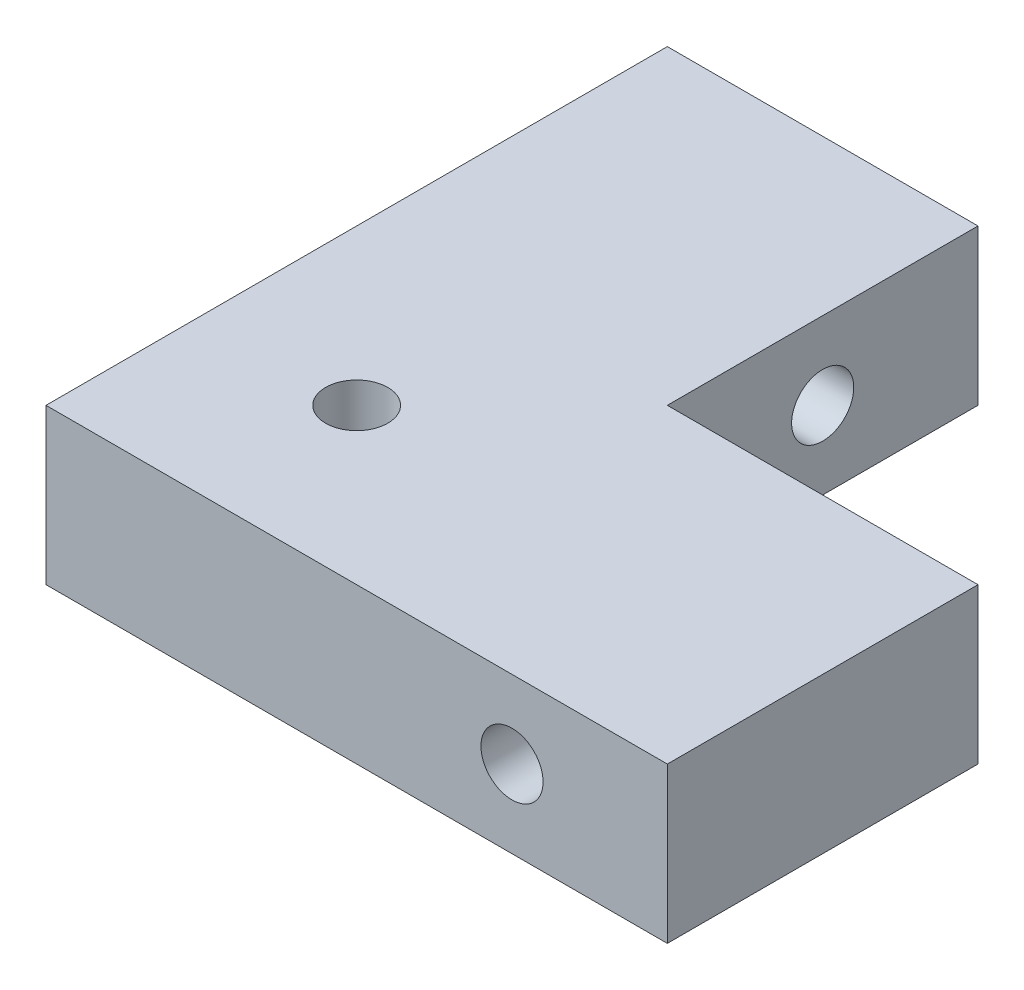
SolidWorks part; units mm, degrees
ref_plane "Plano frontal" through (0, 0, 0) normal (0, 0, 1) x (1, 0, 0)
ref_plane "Plano superior" through (0, 0, 0) normal (0, 1, 0) x (1, 0, 0)
ref_plane "Plano direito" through (0, 0, 0) normal (1, 0, 0) x (0, 0, -1)
sketch "Esboço1" plane through (0, 0, 0) normal (0, 1, 0) x (1, 0, 0)
  line L0 (-70, 36.3043) -> (-70, -43.6957)
  line L1 (-70, -43.6957) -> (10, -43.6957)
  line L2 (10, -43.6957) -> (10, -3.6957)
  line L3 (10, -3.6957) -> (-30, -3.6957)
  line L4 (-30, -3.6957) -> (-30, 36.3043)
  line L5 (-30, 36.3043) -> (-70, 36.3043)
  dimension "D1" = 40
  dimension "D2" = 40
  dimension "D3" = 40
extrude "Ressalto-extrusão1" add sketch "Esboço1" along normal blind 20 contours L0 L1 L2 L3 L4 L5
sketch "Esboço3" plane through (-30, 0, 0) normal (1, 0, 0) x (0, 0, -1)
  line L0 (36.3043, 10) -> (-3.6957, 10) construction
  line L1 (36.3043, 20) -> (36.3043, 0) construction
  line L2 (-3.6957, 20) -> (-3.6957, 0) construction
  circle A0 centre (16.3043, 10) radius 4
  dimension "D1" = 8
sketch "Esboço4" plane through (0, 0, 3.6957) normal (0, 0, -1) x (-1, 0, 0)
  line L0 (30, 10) -> (-10, 10) construction
  line L1 (-10, 20) -> (-10, 0) construction
  circle A0 centre (10, 10) radius 4
  dimension "D1" = 8
extrude "Corte-extrusão1" cut sketch "Esboço3" against normal through all
extrude "Corte-extrusão2" cut sketch "Esboço4" against normal through all
sketch "Esboço5" plane through (0, 0, 0) normal (0, -1, 0) x (1, 0, 0)
  line L0 (-70, -36.3043) -> (-70, 43.6957) construction
  line L1 (-70, 43.6957) -> (10, 43.6957) construction
  circle A0 centre (-50, 23.6957) radius 4
  dimension "D1" = 8
  dimension "D2" = 20
  dimension "D3" = 20
extrude "Corte-extrusão3" cut sketch "Esboço5" against normal through all
